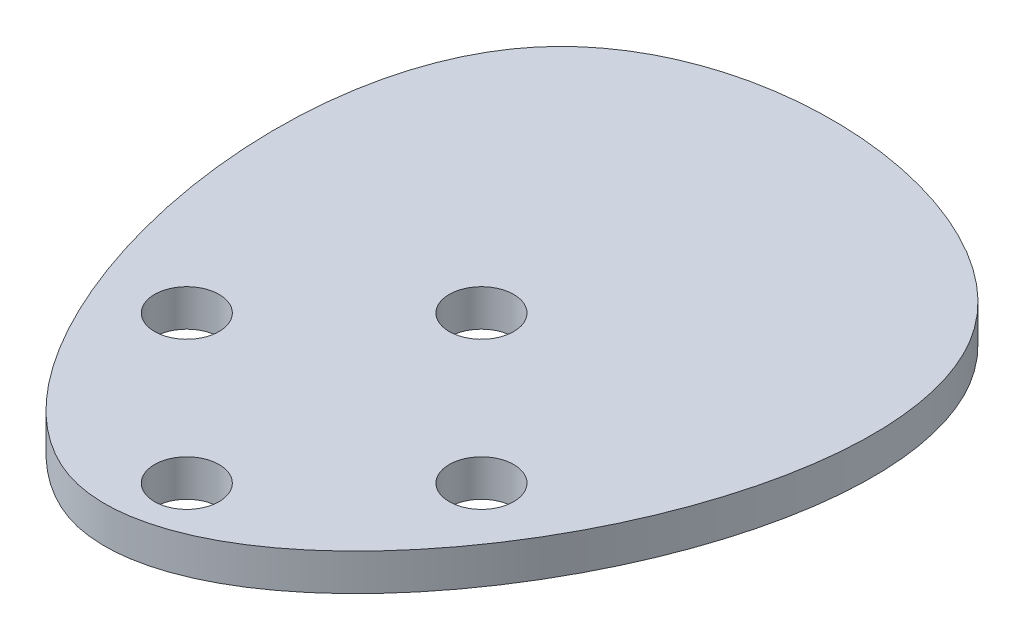
SolidWorks part; units mm, degrees
material "6061 Alloy"
ref_plane "Front Plane" through (0, 0, 0) normal (0, 0, 1) x (1, 0, 0)
ref_plane "Top Plane" through (0, 0, 0) normal (0, 1, 0) x (1, 0, 0)
ref_plane "Right Plane" through (0, 0, 0) normal (1, 0, 0) x (0, 0, -1)
sketch "Sketch1" plane through (0, 0, 0) normal (0, 1, 0) x (1, 0, 0)
  spline S0 degree 3 poles (-11.4801, -10.9897) (9.3752, -11.5343) (28.8068, 25.91) (-23.1702, 30.5658) (-11.4801, -10.9897) (9.3752, -11.5343) (28.8068, 25.91) knots -0.633271 -0.36722 -0.036722 0 0.366729 0.63278 0.963278 1 1.366729 1.63278 1.963278 only from (0, -11.1) to (0, -11.1)
extrude "Extrude1" add sketch "Sketch1" along normal blind 2
sketch "Sketch2" plane through (0, 2, 0) normal (0, 1, 0) x (1, 0, 0)
  circle A0 centre (0, 8) radius 1.75
  circle A1 centre (8, 0) radius 1.75
  circle A2 centre (0, -8) radius 1.75
  circle A3 centre (-8, 0) radius 1.75
  dimension "D1" = 3.5
  dimension "D2" = 3.5
  dimension "D3" = 3.5
  dimension "D4" = 3.5
  dimension "D5" = 8
  dimension "D6" = 8
  dimension "D7" = 8
  dimension "D8" = 8
extrude "Cut-Extrude1" cut sketch "Sketch2" against normal through all
